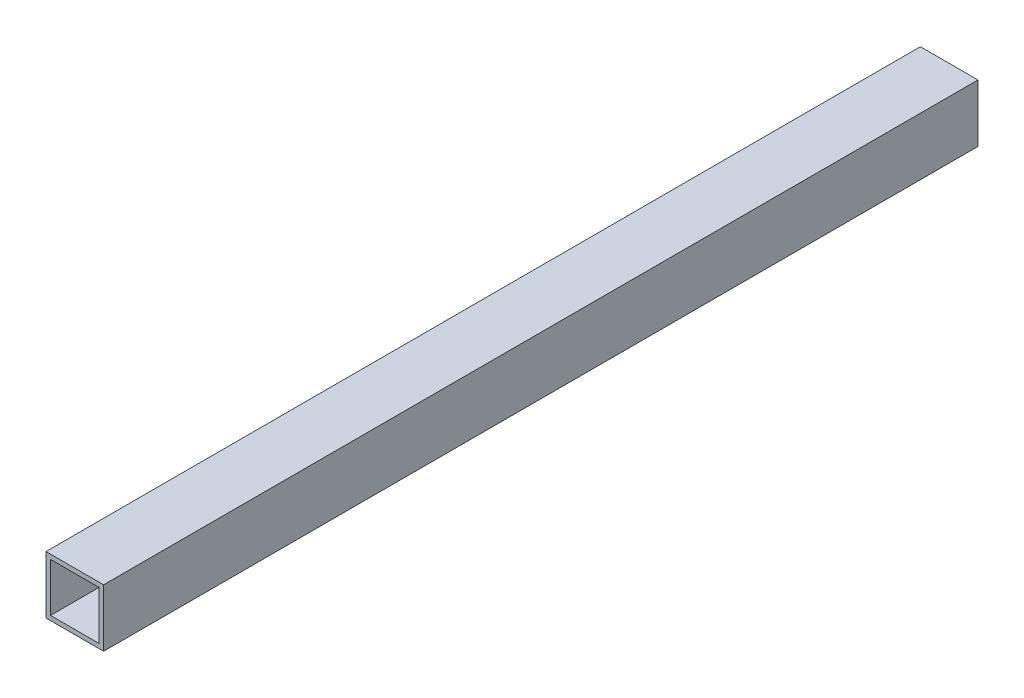
SolidWorks part; units mm, degrees
material "1060 Alloy"
ref_plane "Front Plane" through (0, 0, 0) normal (0, 0, 1) x (1, 0, 0)
ref_plane "Top Plane" through (0, 0, 0) normal (0, 1, 0) x (1, 0, 0)
ref_plane "Right Plane" through (0, 0, 0) normal (1, 0, 0) x (0, 0, -1)
sketch "Sketch1" plane through (0, 0, 0) normal (0, 0, 1) x (1, 0, 0)
  line L1 (-9.55, 9.55) -> (9.55, 9.55)
  line L2 (-9.55, 9.55) -> (-9.55, -9.55)
  line L3 (-9.55, -9.55) -> (9.55, -9.55)
  line L4 (9.55, 9.55) -> (9.55, -9.55)
  line L5 (-9.55, 9.55) -> (9.55, -9.55) construction
  line L6 (-9.55, -9.55) -> (9.55, 9.55) construction
  line L7 (-8.05, 8.05) -> (8.05, 8.05)
  line L8 (-8.05, 8.05) -> (-8.05, -8.05)
  line L9 (-8.05, -8.05) -> (8.05, -8.05)
  line L10 (8.05, 8.05) -> (8.05, -8.05)
  line L11 (-8.05, 8.05) -> (8.05, -8.05) construction
  line L12 (-8.05, -8.05) -> (8.05, 8.05) construction
  point P0 (0, 0)
  point P5 (0, 0)
  dimension "D1" = 19.1
  dimension "D2" = 19.1
  dimension "D3" = 1.5
extrude "Boss-Extrude1" add sketch "Sketch1" along normal blind 290
